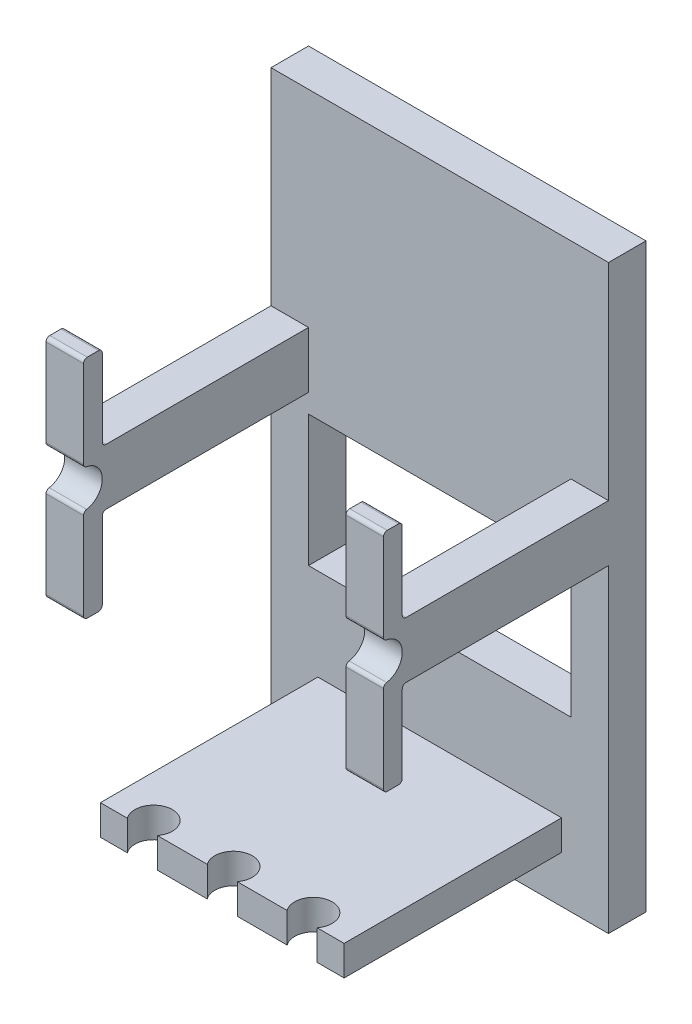
SolidWorks part; units mm, degrees
ref_plane "Front Plane" through (0, 0, 0) normal (1, 0, 0) x (0, 1, 0)
ref_plane "Top Plane" through (0, 0, 0) normal (0, 0, 1) x (0, 1, 0)
ref_plane "Right Plane" through (0, 0, 0) normal (0, 1, 0) x (-1, 0, 0)
sketch "Sketch1" plane through (0, 0, 0) normal (0, 0, 1) x (0, 1, 0)
  line L1 (-62.5, -45) -> (62.5, -45)
  line L2 (-62.5, -45) -> (-62.5, 45)
  line L3 (-62.5, 45) -> (62.5, 45)
  line L4 (62.5, -45) -> (62.5, 45)
  line L5 (0, 45) -> (0, -45) construction
  line L6 (-62.5, 0) -> (62.5, 0) construction
  point P0 (0, 0)
  dimension "D1" = 90
  dimension "D2" = 125
extrude "Boss-Extrude1" add sketch "Sketch1" along normal blind 10 contours L2 L1 L4 L3
sketch "Sketch3" plane through (0, 0, 0) normal (1, 0, 0) x (0, 1, 0)
  line L0 (0, 0) -> (0, 50000) construction
  line L4 (5.9161, 60) -> (7.5, 60)
  line L5 (-7.5, 60) -> (-5.9161, 60)
  line L6 (-7.5, 0) -> (-7.5, 54)
  line L7 (7.5, 0) -> (7.5, 54)
  line L8 (-7.5, 0) -> (7.5, 0)
  line L10 (7.5, 60) -> (7.5, 55) construction
  line L11 (8.5, 55) -> (29.144, 55)
  line L12 (7.5, 60) -> (29.144, 60)
  line L13 (30.144, 59) -> (30.144, 56)
  line L15 (-8.5, 55) -> (-29.144, 55)
  line L16 (-30.144, 59) -> (-30.144, 56)
  line L17 (-7.5, 60) -> (-29.144, 60)
  circle A0 centre (0, 60) radius 62.5 construction
  arc A2 (-4.9301, 59.1667) -> (-5.9161, 60) centre (-5.9161, 59) ccw
  arc A3 (5.9161, 60) -> (4.9301, 59.1667) centre (5.9161, 59) ccw
  arc A4 (29.144, 55) -> (30.144, 56) centre (29.144, 56) ccw
  arc A5 (30.144, 59) -> (29.144, 60) centre (29.144, 59) ccw
  arc A6 (8.5, 55) -> (7.5, 54) centre (8.5, 54) ccw
  arc A7 (-8.5, 55) -> (-7.5, 54) centre (-8.5, 54) cw
  arc A8 (-29.144, 55) -> (-30.144, 56) centre (-29.144, 56) cw
  arc A9 (-30.144, 59) -> (-29.144, 60) centre (-29.144, 59) cw
  arc A10 (-4.9301, 59.1667) -> (4.9301, 59.1667) centre (0, 60) ccw
  point P18 (-5, 60)
  point P21 (5, 60)
  dimension "D2" = 125
  dimension "D9" = 1
  dimension "D4" = 54
  dimension "D1" = 7.5
  dimension "D3" = 7.5
extrude "Boss-Extrude2" add sketch "Sketch3" along normal mid plane 70
sketch "Sketch5" plane through (0, 0, 0) normal (1, 0, 0) x (0, 1, 0)
  line L0 (0, -49.5) -> (0, 49.5) construction
  line L2 (-8.5, 10) -> (8.5, 10)
  line L9 (-7.5, 54) -> (-7.5, 10)
  line L10 (-7.5, 10) -> (7.5, 10)
  line L11 (7.5, 10) -> (7.5, 54)
  line L12 (8.5, 55) -> (29.144, 55)
  line L13 (30.144, 56) -> (30.144, 59)
  line L14 (29.144, 60) -> (5.9161, 60)
  line L15 (-5.9161, 60) -> (-29.144, 60)
  line L16 (-30.144, 59) -> (-30.144, 56)
  line L17 (-29.144, 55) -> (-8.5, 55)
  line L18 (-7.5, 54) -> (-7.5, 11)
  line L19 (-7.5, 10) -> (7.5, 10)
  line L20 (7.5, 11) -> (7.5, 54)
  line L21 (8.5, 55) -> (29.144, 55)
  line L22 (30.144, 56) -> (30.144, 59)
  line L23 (29.144, 60) -> (5.9161, 60)
  line L24 (-5.9161, 60) -> (-29.144, 60)
  line L25 (-30.144, 59) -> (-30.144, 56)
  line L26 (-29.144, 55) -> (-8.5, 55)
  arc A0 (8.5, 10) -> (7.5, 11) centre (8.5, 11) cw
  arc A1 (-8.5, 10) -> (-7.5, 11) centre (-8.5, 11) ccw
  arc A9 (8.5, 55) -> (7.5, 54) centre (8.5, 54) ccw
  arc A10 (29.144, 55) -> (30.144, 56) centre (29.144, 56) ccw
  arc A11 (30.144, 59) -> (29.144, 60) centre (29.144, 59) ccw
  arc A12 (5.9161, 60) -> (4.9301, 59.1667) centre (5.9161, 59) ccw
  arc A13 (-4.9301, 59.1667) -> (4.9301, 59.1667) centre (0, 60) ccw
  arc A14 (-4.9301, 59.1667) -> (-5.9161, 60) centre (-5.9161, 59) ccw
  arc A15 (-29.144, 60) -> (-30.144, 59) centre (-29.144, 59) ccw
  arc A16 (-30.144, 56) -> (-29.144, 55) centre (-29.144, 56) ccw
  arc A17 (-7.5, 54) -> (-8.5, 55) centre (-8.5, 54) ccw
  arc A18 (8.5, 55) -> (7.5, 54) centre (8.5, 54) ccw
  arc A19 (29.144, 55) -> (30.144, 56) centre (29.144, 56) ccw
  arc A20 (30.144, 59) -> (29.144, 60) centre (29.144, 59) ccw
  arc A21 (5.9161, 60) -> (4.9301, 59.1667) centre (5.9161, 59) ccw
  arc A22 (-4.9301, 59.1667) -> (4.9301, 59.1667) centre (0, 60) ccw
  arc A23 (-4.9301, 59.1667) -> (-5.9161, 60) centre (-5.9161, 59) ccw
  arc A24 (-29.144, 60) -> (-30.144, 59) centre (-29.144, 59) ccw
  arc A25 (-30.144, 56) -> (-29.144, 55) centre (-29.144, 56) ccw
  arc A26 (-7.5, 54) -> (-8.5, 55) centre (-8.5, 54) ccw
  dimension "D3" = 1
  dimension "D1" = 0
extrude "Boss-Extrude3" add sketch "Sketch5" along normal mid plane 90 contours A26 L18 A1 L2 A0 L20 A18 L21 A19 L22 A20 L23 A21 A22 A23 L24 A24 L25 A25 L26
sketch "Sketch7" plane through (0, 7.5, 0) normal (0, 1, 0) x (-1, 0, 0)
  line L0 (0, 10) -> (0, 60)
  line L1 (-45, 10) -> (45, 10) construction
  line L2 (-45, 60) -> (45, 60) construction
  line L3 (-45, 10) -> (-35, 10)
  line L5 (-35, 10) -> (-35, 60)
  line L6 (-35, 60) -> (35, 60)
  line L7 (35, 35) -> (35, 60)
  line L8 (0, 60) -> (0, 10) construction
  line L9 (-35, 35) -> (35, 35) construction
  line L10 (-35, 10) -> (35, 10)
  line L11 (-45, 10) -> (45, 10) construction
  line L12 (35, 10) -> (35, 35)
  point P6 (0, 35)
  line M5 (45, 54) -> (-45, 54)
  line M7 (-45, 11) -> (45, 11)
sketch "Sketch11" plane through (0, 0, 10) normal (0, 0, 1) x (1, 0, 0)
  line L1 (-45, -62.5) -> (45, -62.5)
  line L2 (-45, -62.5) -> (-45, -92.5)
  line L3 (-45, -92.5) -> (45, -92.5)
  line L4 (45, -62.5) -> (45, -92.5)
  dimension "D1" = 30
  dimension "D2" = 90
extrude "Boss-Extrude5" add sketch "Sketch11" against normal blind 10
extrude "Cut-Extrude2" cut sketch "Sketch7" against normal through all both and the other way through all contours L5 L0 M7 M5 | L12 L7 L0 M7 M5 | L7 L6 L0 M5 | L6 L5 L0 M5 | L5 L10 L0 M7 | L10 L12 L0 M7
sketch "Sketch17" plane through (45, 0, 0) normal (1, 0, 0) x (0, 1, 0)
  line L1 (-92.5, 0) -> (-31.9249, 0)
  line L2 (-92.5, 0) -> (-92.5, -1.5962)
  line L3 (-92.5, -1.5962) -> (-31.9249, -1.5962)
  line L4 (-31.9249, 0) -> (-31.9249, -1.5962)
  line L5 (-31.9249, -1.5962) -> (62.5, -1.5962)
  line L6 (-31.9249, -1.5962) -> (-31.9249, 0)
  line L7 (-31.9249, 0) -> (62.5, 0)
  line L8 (62.5, -1.5962) -> (62.5, 0)
  arc A0 (-35, -0.6218) -> (-27.5, 12.3686) centre (-31.25, 5.8734) ccw construction
  line M9 (-92.5, 0) -> (62.5, 0)
extrude "Boss-Extrude7" add sketch "Sketch17" against normal up to surface (90 mm away) contours L4 L2 L3 M9 | L5 L8 L4 M9 up to face at (-45, -2.5, 40.6053)
sketch "Sketch18" plane through (45, 0, 0) normal (1, 0, 0) x (0, 1, 0)
  line L0 (-92.5, 10) -> (-92.5, -10)
  line L2 (-92.5, -10) -> (62.5, -10)
  line L3 (-92.5, -10) -> (-92.5, -1.5962)
  line L4 (-92.5, -1.5962) -> (62.5, -1.5962)
  line L5 (62.5, -10) -> (62.5, -1.5962)
  line M6 (-92.5, -1.5962) -> (62.5, -1.5962)
  dimension "D1" = 20
extrude "Boss-Extrude8" add sketch "Sketch18" against normal up to surface (90 mm away) contours L2 L5 L0 M6 up to face at (-45, -2.5, 40.4723)
sketch "Sketch19" plane through (45, 0, 0) normal (1, 0, 0) x (0, 1, 0)
  line L0 (62.5, 10) -> (62.5, -10) construction
  line L1 (-92.5, 10) -> (-8.5, 10)
  line L2 (-92.5, 10) -> (-92.5, 0)
  line L3 (-92.5, 0) -> (-7.5, 0)
  line L4 (62.5, 10) -> (62.5, 0)
  line L5 (-7.5, 11) -> (-7.5, 0)
  line L6 (7.5, 11) -> (7.5, 0)
  line L7 (8.5, 10) -> (62.5, 10)
  line L8 (7.5, 0) -> (62.5, 0)
  arc A0 (7.5, 11) -> (8.5, 10) centre (8.5, 11) ccw construction
  arc A1 (-8.5, 10) -> (-7.5, 11) centre (-8.5, 11) ccw construction
  arc A2 (7.5, 11) -> (8.5, 10) centre (8.5, 11) ccw
  arc A3 (-8.5, 10) -> (-7.5, 11) centre (-8.5, 11) ccw
extrude "Cut-Extrude3" cut sketch "Sketch19" against normal through all both and the other way through all
sketch "Sketch21" plane through (0, 7.5, 0) normal (0, 1, 0) x (-1, 0, 0)
  line L0 (45, 0) -> (-45, 0) construction
  line L1 (-35, 10) -> (35, 10)
  line L2 (-35, 10) -> (-35, 0)
  line L3 (-35, 0) -> (35, 0)
  line L4 (35, 10) -> (35, 0)
  line M7 (35, 10) -> (-35, 10)
  line M11 (-45, 0) -> (45, 0)
extrude "Cut-Extrude4" cut sketch "Sketch21" against normal through all both and the other way through all contours L4 L2 M7 M11
sketch "Sketch22" plane through (0, 0, 0) normal (0, 0, 1) x (1, 0, 0)
  line L0 (0, 0) -> (0, -30) construction
  line L2 (-35, -47.5) -> (35, -47.5)
  line L3 (-35, -47.5) -> (-35, -12.5)
  line L4 (-35, -12.5) -> (35, -12.5)
  line L5 (35, -47.5) -> (35, -12.5)
  line L6 (0, -12.5) -> (0, -47.5) construction
  line L7 (-35, -30) -> (35, -30) construction
  dimension "D1" = 30
  dimension "D2" = 35
  dimension "D3" = 70
extrude "Cut-Extrude5" cut sketch "Sketch22" along normal through all and the other way through all
sketch "Sketch23" plane through (0, 0, 0) normal (0, 0, 1) x (1, 0, 0)
  line L0 (0, 0) -> (0, -76) construction
  line L2 (-32.5, -80) -> (32.5, -80)
  line L3 (-32.5, -80) -> (-32.5, -72)
  line L4 (-32.5, -72) -> (32.5, -72)
  line L5 (32.5, -80) -> (32.5, -72)
  line L6 (0, -72) -> (0, -80) construction
  line L7 (-32.5, -76) -> (32.5, -76) construction
  dimension "D1" = 76
  dimension "D2" = 8
  dimension "D3" = 65
extrude "Boss-Extrude9" add sketch "Sketch23" along normal blind 58
sketch "Sketch24" plane through (0, -80, 0) normal (0, -1, 0) x (1, 0, 0)
  circle A0 centre (0, 55) radius 5
  circle A1 centre (-21.3, 55) radius 5
  circle A2 centre (21.3, 55) radius 5
  dimension "D1" = 10
  dimension "D2" = 10
  dimension "D3" = 10
extrude "Cut-Extrude6" cut sketch "Sketch24" against normal mid plane 58
